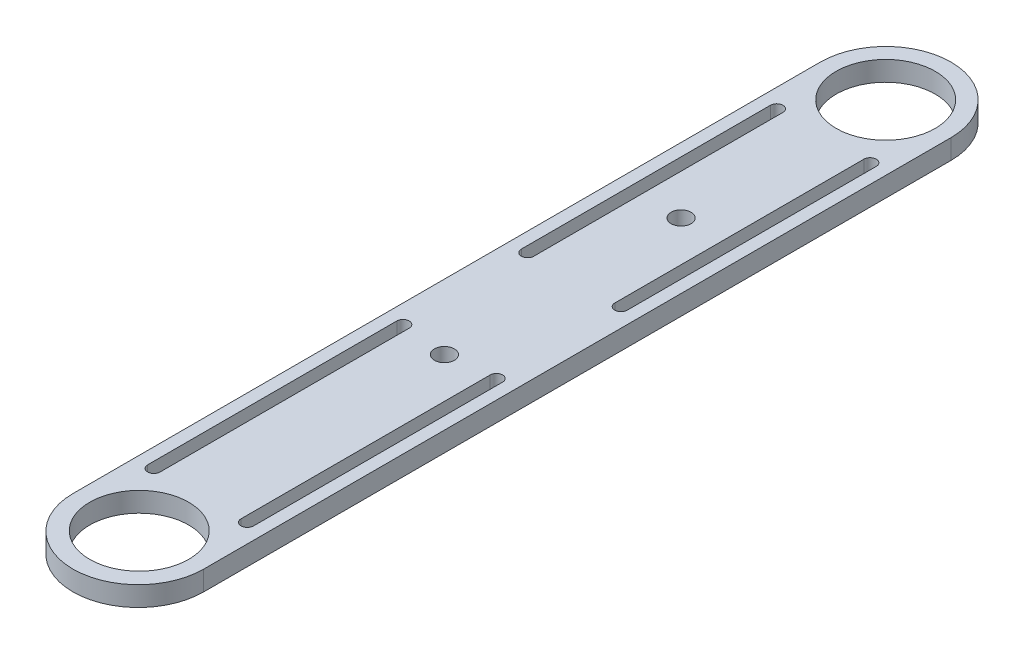
SolidWorks part; units mm, degrees
ref_plane "Front Plane" through (0, 0, 0) normal (0, 0, 1) x (1, 0, 0)
ref_plane "Top Plane" through (0, 0, 0) normal (0, 1, 0) x (1, 0, 0)
ref_plane "Right Plane" through (0, 0, 0) normal (1, 0, 0) x (0, 0, -1)
sketch "Sketch1" plane through (0, 0, 0) normal (0, 1, 0) x (1, 0, 0)
  line L0 (-10.5, 0) -> (-10.5, -120)
  line L1 (10.5, 0) -> (10.5, -120)
  arc A0 (10.5, 0) -> (-10.5, 0) centre (0, 0) ccw
  arc A1 (-10.5, -120) -> (10.5, -120) centre (0, -120) ccw
  dimension "D1" = 10.5
  dimension "D2" = 120
extrude "Boss-Extrude1" add sketch "Sketch1" along normal blind 3.175
sketch "Sketch3" plane through (0, 0, 0) normal (0, -1, 0) x (1, 0, 0)
  line L0 (-8.5, 110) -> (-8.5, 70) construction
  line L1 (-6.5, 70) -> (-6.5, 110) construction
  line L2 (6.5, 110) -> (6.5, 70) construction
  line L3 (8.5, 70) -> (8.5, 110) construction
  line L4 (8.5, 10) -> (8.5, 50) construction
  line L5 (6.5, 50) -> (6.5, 10) construction
  line L6 (-8.5, 50) -> (-8.5, 10) construction
  line L7 (-6.5, 10) -> (-6.5, 50) construction
  line L8 (-8.5, 110) -> (-8.5, 70)
  line L9 (-6.5, 70) -> (-6.5, 110)
  line L10 (6.5, 110) -> (6.5, 70)
  line L11 (8.5, 70) -> (8.5, 110)
  line L12 (8.5, 10) -> (8.5, 50)
  line L13 (6.5, 50) -> (6.5, 10)
  line L14 (-8.5, 50) -> (-8.5, 10)
  line L15 (-6.5, 10) -> (-6.5, 50)
  arc A1 (-8.5, 70) -> (-6.5, 70) centre (-7.5, 70) ccw construction
  arc A2 (8.5, 110) -> (6.5, 110) centre (7.5, 110) ccw construction
  arc A3 (6.5, 70) -> (8.5, 70) centre (7.5, 70) ccw construction
  arc A4 (6.5, 10) -> (8.5, 10) centre (7.5, 10) ccw construction
  arc A5 (8.5, 50) -> (6.5, 50) centre (7.5, 50) ccw construction
  arc A6 (-6.5, 50) -> (-8.5, 50) centre (-7.5, 50) ccw construction
  arc A7 (-8.5, 10) -> (-6.5, 10) centre (-7.5, 10) ccw construction
  arc A8 (-8.5, 70) -> (-6.5, 70) centre (-7.5, 70) ccw
  arc A9 (8.5, 110) -> (6.5, 110) centre (7.5, 110) ccw
  arc A10 (6.5, 70) -> (8.5, 70) centre (7.5, 70) ccw
  arc A11 (6.5, 10) -> (8.5, 10) centre (7.5, 10) ccw
  arc A12 (8.5, 50) -> (6.5, 50) centre (7.5, 50) ccw
  arc A13 (-6.5, 50) -> (-8.5, 50) centre (-7.5, 50) ccw
  arc A14 (-8.5, 10) -> (-6.5, 10) centre (-7.5, 10) ccw
  arc A15 (-6.5, 110) -> (-8.5, 110) centre (-7.5, 110) ccw construction
  arc A16 (-6.5, 110) -> (-8.5, 110) centre (-7.5, 110) ccw
extrude "Cut-Extrude2" cut sketch "Sketch3" against normal through all both and the other way through all
sketch "Sketch5" plane through (0, 3.175, 0) normal (0, 1, 0) x (1, 0, 0)
  circle A0 centre (0, 0) radius 7.95 construction
  circle A1 centre (-0.0032, -119.85) radius 7.95 construction
  circle A2 centre (0, 0) radius 7.95
  circle A3 centre (-0.0032, -119.85) radius 7.95
extrude "Cut-Extrude4" cut sketch "Sketch5" against normal through all both and the other way through all
sketch "Sketch8" plane through (0, 3.175, 0) normal (0, 1, 0) x (1, 0, 0)
  circle A0 centre (0, -32.85) radius 1.6 construction
  circle A1 centre (0, -70.85) radius 1.6 construction
  circle A2 centre (0, -32.85) radius 1.6
  circle A3 centre (0, -70.85) radius 1.6
extrude "Cut-Extrude6" cut sketch "Sketch8" against normal blind 10
